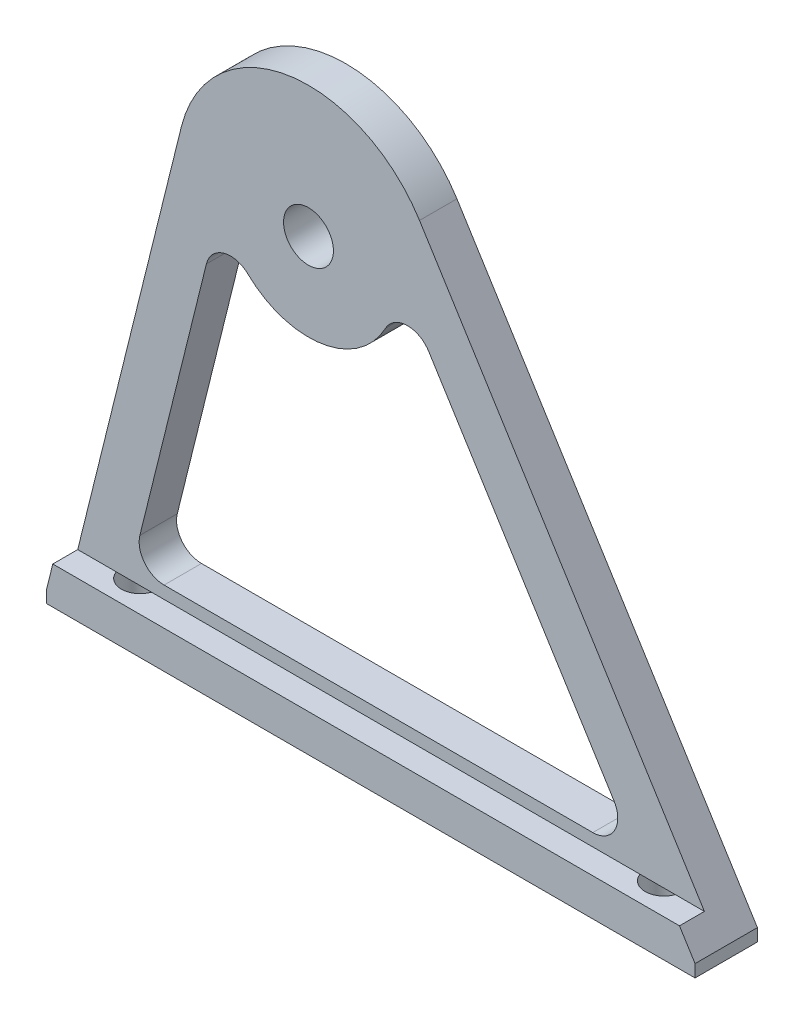
SolidWorks part; units mm, degrees
ref_plane "前视基准面" through (0, 0, 0) normal (0, 0, 1) x (1, 0, 0)
ref_plane "上视基准面" through (0, 0, 0) normal (0, 1, 0) x (1, 0, 0)
ref_plane "右视基准面" through (0, 0, 0) normal (1, 0, 0) x (0, 0, -1)
sketch "草图1" plane through (0, 0, 0) normal (0, 0, 1) x (1, 0, 0)
  line L0 (-10.1914, 2.5269) -> (-19, -33)
  line L1 (-8.4527, -7.0818) -> (-13.5198, -27.5187)
  line L2 (33, -33) -> (8.9047, 5.5638)
  line L3 (-19, -33) -> (-19, -34)
  line L4 (-19, -34) -> (33, -34)
  line L5 (33, -34) -> (33, -33)
  line L6 (-11.5786, -30) -> (22.801, -30)
  line L7 (24.4972, -26.9402) -> (9.6425, -3.1658)
  line L8 (-8.4527, -7.0818) -> (-8.1847, -6.0009)
  arc A0 (8.9047, 5.5638) -> (-10.1914, 2.5269) centre (0, 0) ccw
  arc A1 (-4.856, -5.0417) -> (6.1805, -3.2865) centre (0, 0) ccw
  arc A2 (22.801, -30) -> (24.4972, -26.9402) centre (22.801, -28) ccw
  arc A3 (-11.5786, -30) -> (-13.5198, -27.5187) centre (-11.5786, -28) cw
  arc A4 (-8.1847, -6.0009) -> (-4.856, -5.0417) centre (-6.2435, -6.4822) cw
  arc A5 (9.6425, -3.1658) -> (6.1805, -3.2865) centre (7.9464, -4.2255) ccw
  circle A6 centre (0, 0) radius 2
  dimension "D1" = 14
  dimension "D2" = 21
  dimension "D9" = 2
  dimension "D10" = 2
  dimension "D13" = 4
  dimension "D3" = 4
  dimension "D4" = 19
  dimension "D5" = 52
  dimension "D6" = 1
  dimension "D7" = 4
  dimension "D8" = 4
  dimension "D11" = 34
  dimension "D12" = 1
extrude "凸台-拉伸1" add sketch "草图1" along normal blind 5
sketch "草图2" plane through (0, 0, 5) normal (0, 0, 1) x (1, 0, 0)
  line L0 (-19, -34) -> (33, -34) construction
  line L1 (54.2962, -31) -> (-51.2945, -31)
  line L2 (54.2962, -31) -> (54.2962, 22.7343)
  line L3 (54.2962, 22.7343) -> (-51.2945, 22.7343)
  line L4 (-51.2945, -31) -> (-51.2945, 22.7343)
  line L5 (54.2962, -31) -> (-51.2945, 22.7343) construction
  line L6 (54.2962, 22.7343) -> (-51.2945, -31) construction
  point P0 (1.5009, -4.1328)
  dimension "D1" = 3
extrude "切除-拉伸1" cut sketch "草图2" against normal blind 2
sketch "草图4" plane through (0, -34, 0) normal (0, -1, 0) x (-1, 0, 0)
  line L0 (19, -2.5) -> (-33, -2.5) construction
  line L1 (19, -5) -> (19, 0) construction
  line L2 (-33, -5) -> (-33, 0) construction
  circle A0 centre (14, -2.5) radius 1.5
  circle A1 centre (-28, -2.5) radius 1.5
  dimension "D1" = 3
  dimension "D2" = 3
  dimension "D3" = 42
  dimension "D4" = 5
extrude "切除-拉伸2" cut sketch "草图4" against normal blind 3
